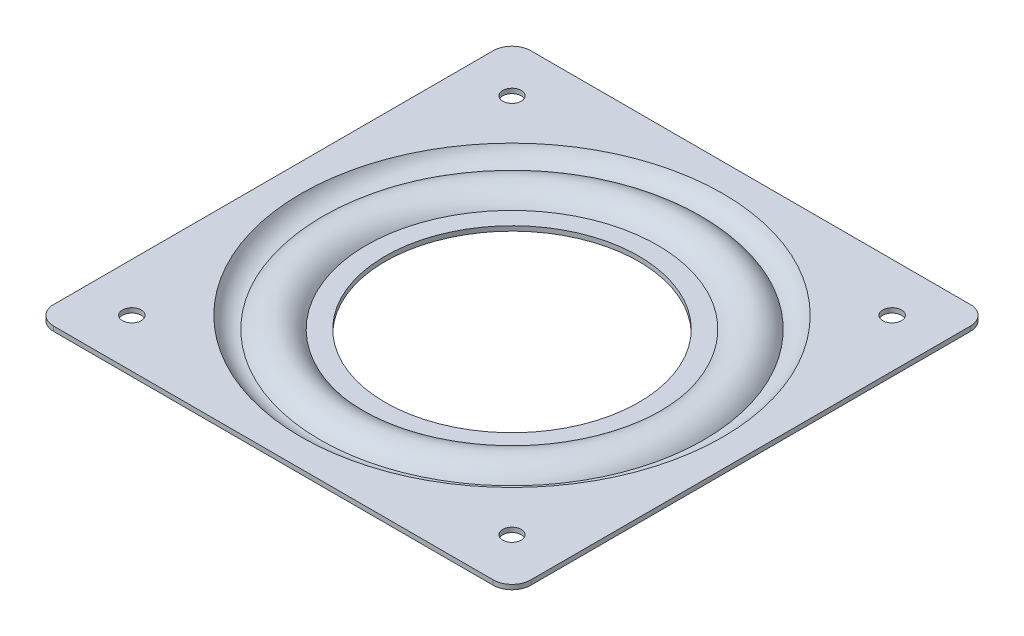
SolidWorks part; units mm, degrees
ref_plane "前视基准面" through (0, 0, 0) normal (0, 0, 1) x (1, 0, 0)
ref_plane "上视基准面" through (0, 0, 0) normal (0, 1, 0) x (1, 0, 0)
ref_plane "右视基准面" through (0, 0, 0) normal (1, 0, 0) x (0, 0, -1)
sketch "草图1" plane through (0, 0, 0) normal (0, 0, 1) x (1, 0, 0)
  line L0 (-36.7805, 0) -> (-35.9228, 0)
  line L1 (0, 6.9172) -> (0, -6.9172) construction
  line L2 (-31, -2.5698) -> (-27, -2.5698)
  line L3 (-35.9228, 0) -> (0, 0) construction
  line L4 (0, 0) -> (43.3864, 0) construction
  line L5 (-43.3864, 0) -> (-36.7805, 0) construction
  line L6 (-31.5531, -3.5698) -> (-27, -3.5698)
  line L7 (-27, -2.5698) -> (-27, -3.5698)
  line L8 (-44.9105, 0) -> (-45.8139, -0.4289)
  arc A0 (-44.9105, 0) -> (-40.8455, -2.5698) centre (-40.8455, 1.9302) ccw
  arc A1 (-40.8455, -2.5698) -> (-31, -2.5698) centre (-35.9228, -6) cw
  arc A2 (-40.8455, -2.5698) -> (-36.8127, -0.0664) centre (-40.8455, 1.9302) ccw construction
  arc A3 (-36.8127, -0.0664) -> (-36.7805, 0) centre (-40.8455, 1.9302) ccw
  arc A4 (-45.8139, -0.4289) -> (-40.2759, -3.5402) centre (-40.8455, 1.9302) ccw
  arc A5 (-40.2759, -3.5402) -> (-31.5531, -3.5698) centre (-35.9228, -6) cw
  point P4 (0, 0)
  point P8 (0, 0)
  dimension "D1" = 4.5
  dimension "D2" = 6
  dimension "D3" = 27
  dimension "D4" = 4
revolve "旋转1" add sketch "草图1" angle 360 about L1
sketch "草图2" plane through (0, 0, 0) normal (0, 1, 0) x (1, 0, 0)
  line L1 (-46.8, 50.8) -> (46.8, 50.8)
  line L2 (-50.8, 46.8) -> (-50.8, -46.8)
  line L3 (-46.8, -50.8) -> (46.8, -50.8)
  line L4 (50.8, 46.8) -> (50.8, -46.8)
  line L5 (-50.8, 50.8) -> (50.8, -50.8) construction
  line L6 (-50.8, -50.8) -> (50.8, 50.8) construction
  circle A0 centre (0, 0) radius 44.9105 construction
  circle A1 centre (0, 0) radius 44.9105
  arc A2 (-46.8, 50.8) -> (-50.8, 46.8) centre (-46.8, 46.8) ccw
  circle A3 centre (-40.48, 40.48) radius 1.985
  circle A4 centre (40.48, 40.48) radius 1.985
  arc A5 (50.8, 46.8) -> (46.8, 50.8) centre (46.8, 46.8) ccw
  circle A6 centre (40.48, -40.48) radius 1.985
  arc A7 (46.8, -50.8) -> (50.8, -46.8) centre (46.8, -46.8) ccw
  circle A8 centre (-40.48, -40.48) radius 1.985
  arc A9 (-50.8, -46.8) -> (-46.8, -50.8) centre (-46.8, -46.8) ccw
  point P14 (0, 0)
  point P32 (0, 0)
  dimension "D3" = 4
  dimension "D4" = 3.97
  dimension "D5" = 4
  dimension "D1" = 90
  dimension "D2" = 101.6
  dimension "D6" = 57.2474
extrude "凸台-拉伸1" add sketch "草图2" against normal blind 1
